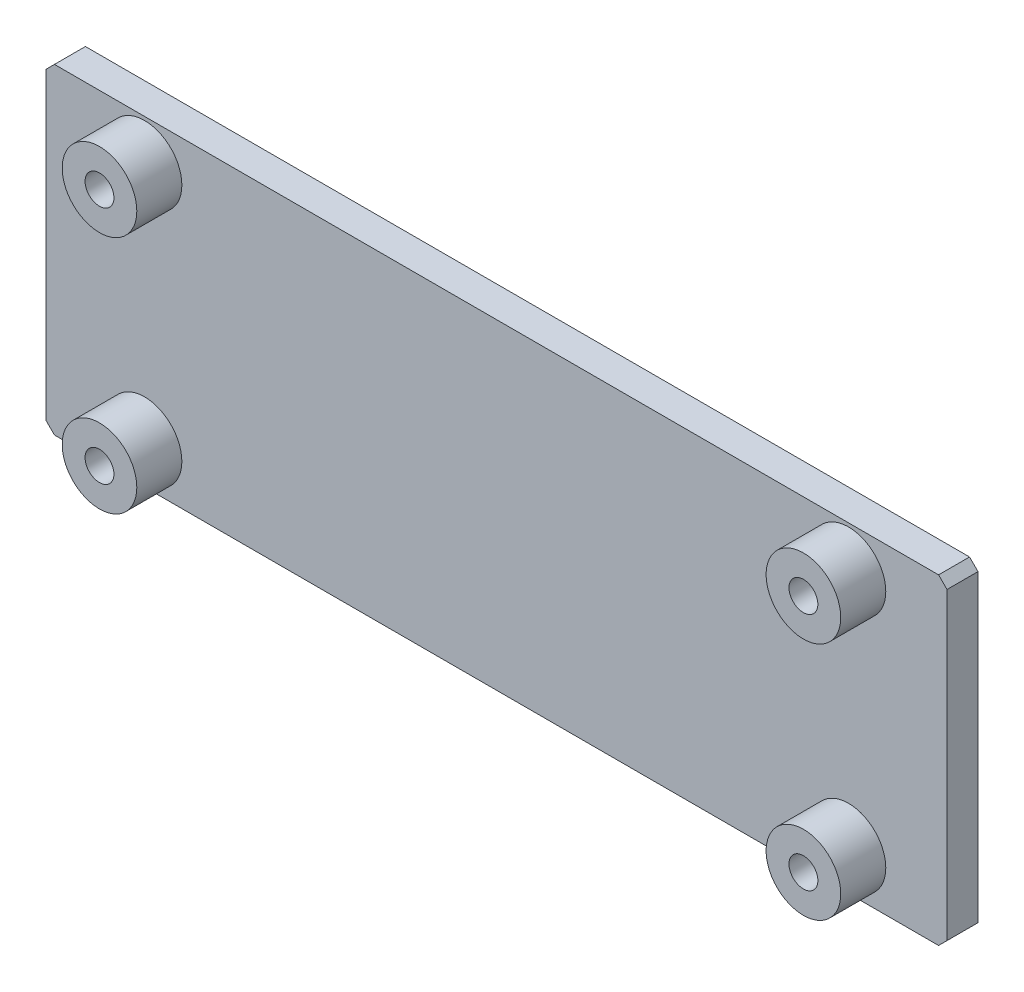
SolidWorks part; units mm, degrees
ref_plane "前视基准面" through (0, 0, 0) normal (0, 0, 1) x (1, 0, 0)
ref_plane "上视基准面" through (0, 0, 0) normal (0, 1, 0) x (1, 0, 0)
ref_plane "右视基准面" through (0, 0, 0) normal (1, 0, 0) x (0, 0, -1)
other "Configuration Table"
sketch "Flat back of separately printed slide-in plate profile" plane through (0, 0, 0) normal (0, 0, 1) x (1, 0, 0)
  line L0 (-31.4, -11.4) -> (31.4, -11.4)
  line L1 (31.4, -11.4) -> (32, -10.8)
  line L2 (32, -10.8) -> (32, 10.8)
  line L3 (32, 10.8) -> (31.4, 11.4)
  line L4 (31.4, 11.4) -> (-31.4, 11.4)
  line L5 (-31.4, 11.4) -> (-32, 10.8)
  line L6 (-32, 10.8) -> (-32, -10.8)
  line L7 (-32, -10.8) -> (-31.4, -11.4)
extrude "Flat back of separately printed slide-in plate" add sketch "Flat back of separately printed slide-in plate profile" along normal blind 1
sketch "Plate rim with blind D2.05 pilot bottoms profile" plane through (0, 0, 0) normal (0, 0, 1) x (1, 0, 0)
  line L0 (-31.4, -11.4) -> (31.4, -11.4)
  line L1 (31.4, -11.4) -> (32, -10.8)
  line L2 (32, -10.8) -> (32, 10.8)
  line L3 (32, 10.8) -> (31.4, 11.4)
  line L4 (31.4, 11.4) -> (-31.4, 11.4)
  line L5 (-31.4, 11.4) -> (-32, 10.8)
  line L6 (-32, 10.8) -> (-32, -10.8)
  line L7 (-32, -10.8) -> (-31.4, -11.4)
  circle A0 centre (-25, -8.5) radius 1.025
  circle A1 centre (-25, 8.5) radius 1.025
  circle A2 centre (25, -8.5) radius 1.025
  circle A3 centre (25, 8.5) radius 1.025
extrude "Plate rim with blind D2.05 pilot bottoms" add sketch "Plate rim with blind D2.05 pilot bottoms profile" along normal blind 1.2 from offset 1
sketch "Raised power board supports - no nuts behind slide profile" plane through (0, 0, 0) normal (0, 0, 1) x (1, 0, 0)
  circle A0 centre (-25, -8.5) radius 2.65
  circle A1 centre (-25, 8.5) radius 2.65
  circle A2 centre (25, -8.5) radius 2.65
  circle A3 centre (25, 8.5) radius 2.65
  circle A4 centre (-25, -8.5) radius 1.025
  circle A5 centre (-25, 8.5) radius 1.025
  circle A6 centre (25, -8.5) radius 1.025
  circle A7 centre (25, 8.5) radius 1.025
extrude "Raised power board supports - no nuts behind slide" add sketch "Raised power board supports - no nuts behind slide profile" along normal blind 3.2 from offset 2.2
